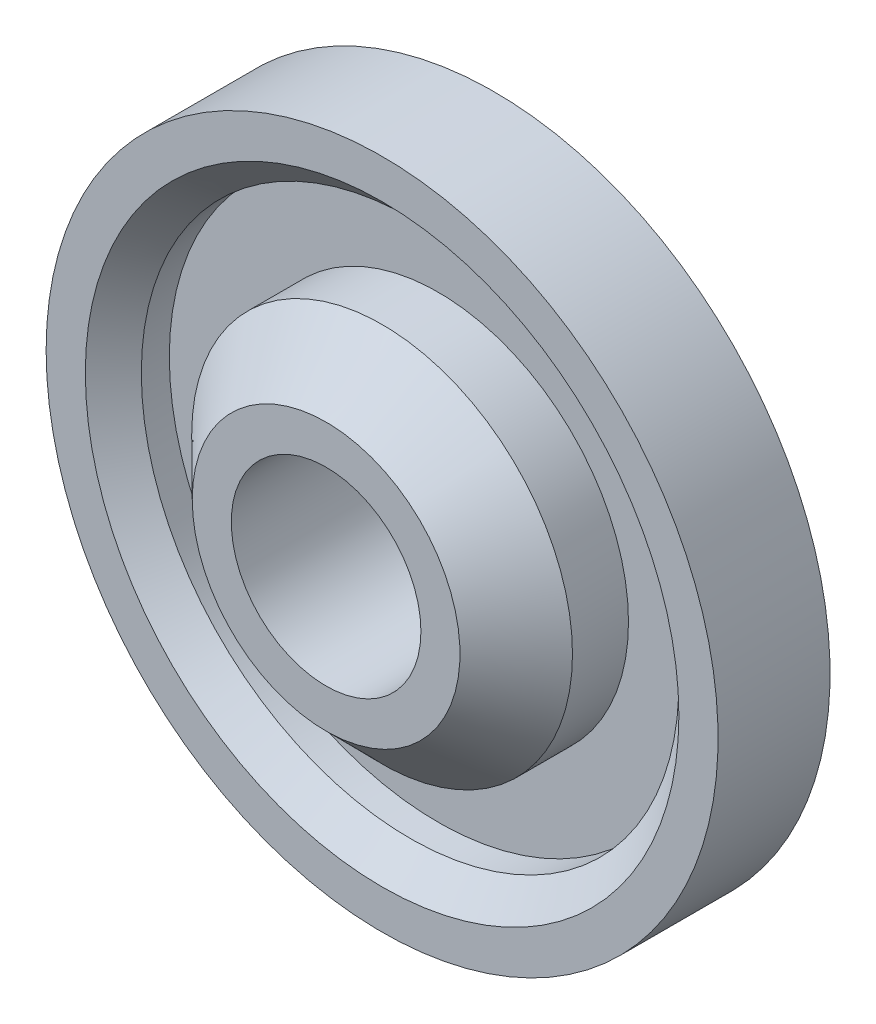
SolidWorks part; units mm, degrees
material "ABS"
ref_plane "Front Plane" through (0, 0, 0) normal (0, 0, 1) x (1, 0, 0)
ref_plane "Top Plane" through (0, 0, 0) normal (0, 1, 0) x (1, 0, 0)
ref_plane "Right Plane" through (0, 0, 0) normal (1, 0, 0) x (0, 0, -1)
sketch "Sketch1" plane through (0, 0, 0) normal (0, 1, 0) x (1, 0, 0)
  line L0 (0, 0) -> (6, 0)
  line L1 (6, 0) -> (6, -2)
  line L2 (6, -2) -> (5.3, -2)
  line L3 (5.3, -2) -> (4.8, -1.5)
  line L4 (4.8, -1.5) -> (4.8, -1)
  line L5 (4.8, -1) -> (3.4, -1)
  line L6 (3.4, -1) -> (3.4, -2)
  line L7 (3.4, -2) -> (2.3906, -3)
  line L8 (2.3906, -3) -> (0, -3)
  line L9 (0, 0) -> (0, -3.4765) construction
  line L10 (0, -3) -> (0, 0)
  dimension "D1" = 6
  dimension "D2" = 2
  dimension "D3" = 0.7
  dimension "D4" = 1.4
  dimension "D5" = 3
  dimension "D6" = 2.3906
  dimension "D7" = 1
  dimension "D8" = 1.2
  dimension "D9" = 0.5
  dimension "D10" = 1
revolve "Revolve1" add sketch "Sketch1" angle 360 about L9
sketch "Sketch2" plane through (0, 0, 3) normal (0, 0, 1) x (1, 0, 0)
  circle A0 centre (0, 0) radius 1.6933
  dimension "D1" = 3.3866
extrude "Cut-Extrude1" cut sketch "Sketch2" against normal through all
